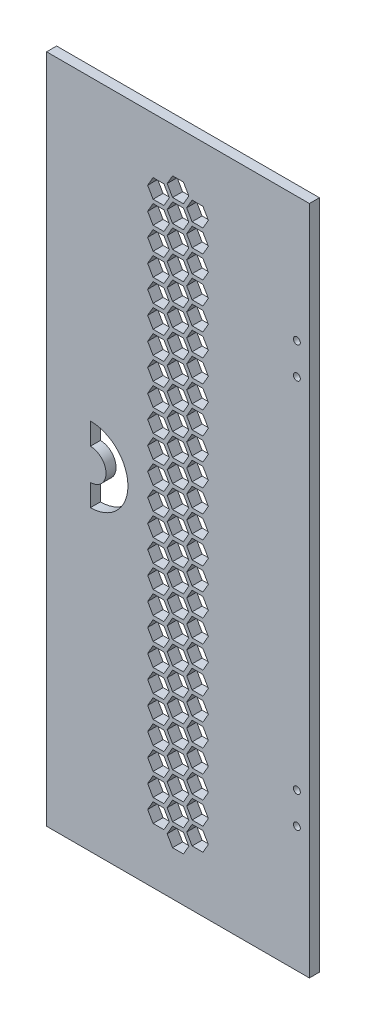
SolidWorks part; units mm, degrees
ref_plane "Front Plane" through (0, 0, 0) normal (0, 0, 1) x (1, 0, 0)
ref_plane "Top Plane" through (0, 0, 0) normal (0, 1, 0) x (1, 0, 0)
ref_plane "Right Plane" through (0, 0, 0) normal (1, 0, 0) x (0, 0, -1)
sketch "Sketch1" plane through (0, 0, 0) normal (0, 0, 1) x (1, 0, 0)
  line L1 (-105, 268) -> (105, 268)
  line L2 (-105, 268) -> (-105, -268)
  line L3 (-105, -268) -> (105, -268)
  line L4 (105, 268) -> (105, -268)
  line L5 (-105, 268) -> (105, -268) construction
  line L6 (-105, -268) -> (105, 268) construction
  circle A10 centre (95, -168) radius 2.75
  circle A11 centre (95, 168) radius 2.75
  circle A12 centre (95, 143) radius 2.75
  circle A13 centre (95, -143) radius 2.75
  point P0 (0, 0)
  point P41 (-6.0047, 6.0048)
  dimension "D3" = 100
  dimension "D1" = 536
  dimension "D2" = 10
  dimension "D4" = 100
  dimension "D7" = 311
  dimension "D5" = 25
  dimension "D8" = 25
  dimension "D9" = 210
extrude "Boss-Extrude1" add sketch "Sketch1" along normal blind 8
sketch "Sketch3" plane through (0, 0, 8) normal (0, 0, 1) x (1, 0, 0)
  line L0 (0, 207) -> (0, 225) construction
  line L1 (24.2487, 216) -> (19.9186, 223.5)
  line L2 (-6.9282, 216) -> (-11.2583, 223.5)
  line L3 (-11.2583, 223.5) -> (-19.9186, 223.5)
  line L4 (-19.9186, 223.5) -> (-24.2487, 216)
  line L5 (19.9186, 223.5) -> (11.2583, 223.5)
  line L6 (11.2583, 223.5) -> (6.9282, 216)
  line L7 (6.9282, 216) -> (11.2583, 208.5)
  line L8 (-24.2487, 216) -> (-19.9186, 208.5)
  line L9 (-19.9186, 208.5) -> (-11.2583, 208.5)
  line L10 (-11.2583, 208.5) -> (-6.9282, 216)
  line L11 (8.6603, 207) -> (4.3301, 214.5)
  line L12 (24.2487, 72) -> (19.9186, 79.5)
  line L13 (-6.9282, 72) -> (-11.2583, 79.5)
  line L14 (-11.2583, 79.5) -> (-19.9186, 79.5)
  line L15 (-19.9186, 79.5) -> (-24.2487, 72)
  line L16 (19.9186, 79.5) -> (11.2583, 79.5)
  line L17 (11.2583, 79.5) -> (6.9282, 72)
  line L18 (6.9282, 72) -> (11.2583, 64.5)
  line L19 (-24.2487, 72) -> (-19.9186, 64.5)
  line L20 (4.3301, 214.5) -> (-4.3301, 214.5)
  line L21 (-4.3301, 214.5) -> (-8.6603, 207)
  line L22 (-8.6603, 207) -> (-4.3301, 199.5)
  line L23 (-4.3301, 199.5) -> (4.3301, 199.5)
  line L24 (4.3301, 199.5) -> (8.6603, 207)
  line L25 (8.6603, 225) -> (4.3301, 232.5)
  line L26 (4.3301, 232.5) -> (-4.3301, 232.5)
  line L27 (-4.3301, 232.5) -> (-8.6603, 225)
  line L28 (-8.6603, 225) -> (-4.3301, 217.5)
  line L29 (-4.3301, 217.5) -> (4.3301, 217.5)
  line L30 (4.3301, 217.5) -> (8.6603, 225)
  line L31 (11.2583, 208.5) -> (19.9186, 208.5)
  line L32 (19.9186, 208.5) -> (24.2487, 216)
  line L33 (0, 225) -> (15.5885, 216) construction
  line L34 (15.5885, 216) -> (0, 207) construction
  line L35 (0, 207) -> (-15.5885, 216) construction
  line L36 (-15.5885, 216) -> (0, 225) construction
  line L37 (24.2487, 198) -> (19.9186, 205.5)
  line L38 (-6.9282, 198) -> (-11.2583, 205.5)
  line L39 (-11.2583, 205.5) -> (-19.9186, 205.5)
  line L40 (-19.9186, 205.5) -> (-24.2487, 198)
  line L41 (19.9186, 205.5) -> (11.2583, 205.5)
  line L42 (11.2583, 205.5) -> (6.9282, 198)
  line L43 (6.9282, 198) -> (11.2583, 190.5)
  line L44 (-24.2487, 198) -> (-19.9186, 190.5)
  line L45 (-19.9186, 190.5) -> (-11.2583, 190.5)
  line L46 (-11.2583, 190.5) -> (-6.9282, 198)
  line L47 (8.6603, 189) -> (4.3301, 196.5)
  line L48 (4.3301, 196.5) -> (-4.3301, 196.5)
  line L49 (-4.3301, 196.5) -> (-8.6603, 189)
  line L50 (-8.6603, 189) -> (-4.3301, 181.5)
  line L51 (-4.3301, 181.5) -> (4.3301, 181.5)
  line L52 (4.3301, 181.5) -> (8.6603, 189)
  line L53 (11.2583, 190.5) -> (19.9186, 190.5)
  line L54 (19.9186, 190.5) -> (24.2487, 198)
  line L55 (15.5885, 198) -> (0, 189) construction
  line L56 (0, 189) -> (-15.5885, 198) construction
  line L57 (24.2487, 180) -> (19.9186, 187.5)
  line L58 (-6.9282, 180) -> (-11.2583, 187.5)
  line L59 (-11.2583, 187.5) -> (-19.9186, 187.5)
  line L60 (-19.9186, 187.5) -> (-24.2487, 180)
  line L61 (19.9186, 187.5) -> (11.2583, 187.5)
  line L62 (11.2583, 187.5) -> (6.9282, 180)
  line L63 (6.9282, 180) -> (11.2583, 172.5)
  line L64 (-24.2487, 180) -> (-19.9186, 172.5)
  line L65 (-19.9186, 172.5) -> (-11.2583, 172.5)
  line L66 (-11.2583, 172.5) -> (-6.9282, 180)
  line L67 (8.6603, 171) -> (4.3301, 178.5)
  line L68 (4.3301, 178.5) -> (-4.3301, 178.5)
  line L69 (-4.3301, 178.5) -> (-8.6603, 171)
  line L70 (-8.6603, 171) -> (-4.3301, 163.5)
  line L71 (-4.3301, 163.5) -> (4.3301, 163.5)
  line L72 (4.3301, 163.5) -> (8.6603, 171)
  line L73 (11.2583, 172.5) -> (19.9186, 172.5)
  line L74 (19.9186, 172.5) -> (24.2487, 180)
  line L75 (15.5885, 180) -> (0, 171) construction
  line L76 (0, 171) -> (-15.5885, 180) construction
  line L77 (24.2487, 162) -> (19.9186, 169.5)
  line L78 (-6.9282, 162) -> (-11.2583, 169.5)
  line L79 (-11.2583, 169.5) -> (-19.9186, 169.5)
  line L80 (-19.9186, 169.5) -> (-24.2487, 162)
  line L81 (19.9186, 169.5) -> (11.2583, 169.5)
  line L82 (11.2583, 169.5) -> (6.9282, 162)
  line L83 (6.9282, 162) -> (11.2583, 154.5)
  line L84 (-24.2487, 162) -> (-19.9186, 154.5)
  line L85 (-19.9186, 154.5) -> (-11.2583, 154.5)
  line L86 (-11.2583, 154.5) -> (-6.9282, 162)
  line L87 (8.6603, 153) -> (4.3301, 160.5)
  line L88 (4.3301, 160.5) -> (-4.3301, 160.5)
  line L89 (-4.3301, 160.5) -> (-8.6603, 153)
  line L90 (-8.6603, 153) -> (-4.3301, 145.5)
  line L91 (-4.3301, 145.5) -> (4.3301, 145.5)
  line L92 (4.3301, 145.5) -> (8.6603, 153)
  line L93 (11.2583, 154.5) -> (19.9186, 154.5)
  line L94 (19.9186, 154.5) -> (24.2487, 162)
  line L95 (15.5885, 162) -> (0, 153) construction
  line L96 (0, 153) -> (-15.5885, 162) construction
  line L97 (24.2487, 144) -> (19.9186, 151.5)
  line L98 (-6.9282, 144) -> (-11.2583, 151.5)
  line L99 (-11.2583, 151.5) -> (-19.9186, 151.5)
  line L100 (-19.9186, 151.5) -> (-24.2487, 144)
  line L101 (19.9186, 151.5) -> (11.2583, 151.5)
  line L102 (11.2583, 151.5) -> (6.9282, 144)
  line L103 (6.9282, 144) -> (11.2583, 136.5)
  line L104 (-24.2487, 144) -> (-19.9186, 136.5)
  line L105 (-19.9186, 136.5) -> (-11.2583, 136.5)
  line L106 (-11.2583, 136.5) -> (-6.9282, 144)
  line L107 (8.6603, 135) -> (4.3301, 142.5)
  line L108 (4.3301, 142.5) -> (-4.3301, 142.5)
  line L109 (-4.3301, 142.5) -> (-8.6603, 135)
  line L110 (-8.6603, 135) -> (-4.3301, 127.5)
  line L111 (-4.3301, 127.5) -> (4.3301, 127.5)
  line L112 (4.3301, 127.5) -> (8.6603, 135)
  line L113 (11.2583, 136.5) -> (19.9186, 136.5)
  line L114 (19.9186, 136.5) -> (24.2487, 144)
  line L115 (15.5885, 144) -> (0, 135) construction
  line L116 (0, 135) -> (-15.5885, 144) construction
  line L117 (24.2487, 126) -> (19.9186, 133.5)
  line L118 (-6.9282, 126) -> (-11.2583, 133.5)
  line L119 (-11.2583, 133.5) -> (-19.9186, 133.5)
  line L120 (-19.9186, 133.5) -> (-24.2487, 126)
  line L121 (19.9186, 133.5) -> (11.2583, 133.5)
  line L122 (11.2583, 133.5) -> (6.9282, 126)
  line L123 (6.9282, 126) -> (11.2583, 118.5)
  line L124 (-24.2487, 126) -> (-19.9186, 118.5)
  line L125 (-19.9186, 118.5) -> (-11.2583, 118.5)
  line L126 (-11.2583, 118.5) -> (-6.9282, 126)
  line L127 (8.6603, 117) -> (4.3301, 124.5)
  line L128 (4.3301, 124.5) -> (-4.3301, 124.5)
  line L129 (-4.3301, 124.5) -> (-8.6603, 117)
  line L130 (-8.6603, 117) -> (-4.3301, 109.5)
  line L131 (-4.3301, 109.5) -> (4.3301, 109.5)
  line L132 (4.3301, 109.5) -> (8.6603, 117)
  line L133 (11.2583, 118.5) -> (19.9186, 118.5)
  line L134 (19.9186, 118.5) -> (24.2487, 126)
  line L135 (15.5885, 126) -> (0, 117) construction
  line L136 (0, 117) -> (-15.5885, 126) construction
  line L137 (24.2487, 108) -> (19.9186, 115.5)
  line L138 (-6.9282, 108) -> (-11.2583, 115.5)
  line L139 (-11.2583, 115.5) -> (-19.9186, 115.5)
  line L140 (-19.9186, 115.5) -> (-24.2487, 108)
  line L141 (19.9186, 115.5) -> (11.2583, 115.5)
  line L142 (11.2583, 115.5) -> (6.9282, 108)
  line L143 (6.9282, 108) -> (11.2583, 100.5)
  line L144 (-24.2487, 108) -> (-19.9186, 100.5)
  line L145 (-19.9186, 100.5) -> (-11.2583, 100.5)
  line L146 (-11.2583, 100.5) -> (-6.9282, 108)
  line L147 (8.6603, 99) -> (4.3301, 106.5)
  line L148 (4.3301, 106.5) -> (-4.3301, 106.5)
  line L149 (-4.3301, 106.5) -> (-8.6603, 99)
  line L150 (-8.6603, 99) -> (-4.3301, 91.5)
  line L151 (-4.3301, 91.5) -> (4.3301, 91.5)
  line L152 (4.3301, 91.5) -> (8.6603, 99)
  line L153 (11.2583, 100.5) -> (19.9186, 100.5)
  line L154 (19.9186, 100.5) -> (24.2487, 108)
  line L155 (15.5885, 108) -> (0, 99) construction
  line L156 (0, 99) -> (-15.5885, 108) construction
  line L157 (24.2487, 90) -> (19.9186, 97.5)
  line L158 (-6.9282, 90) -> (-11.2583, 97.5)
  line L159 (-11.2583, 97.5) -> (-19.9186, 97.5)
  line L160 (-19.9186, 97.5) -> (-24.2487, 90)
  line L161 (19.9186, 97.5) -> (11.2583, 97.5)
  line L162 (11.2583, 97.5) -> (6.9282, 90)
  line L163 (6.9282, 90) -> (11.2583, 82.5)
  line L164 (-24.2487, 90) -> (-19.9186, 82.5)
  line L165 (-19.9186, 82.5) -> (-11.2583, 82.5)
  line L166 (-11.2583, 82.5) -> (-6.9282, 90)
  line L167 (8.6603, 81) -> (4.3301, 88.5)
  line L168 (4.3301, 88.5) -> (-4.3301, 88.5)
  line L169 (-4.3301, 88.5) -> (-8.6603, 81)
  line L170 (-8.6603, 81) -> (-4.3301, 73.5)
  line L171 (-4.3301, 73.5) -> (4.3301, 73.5)
  line L172 (4.3301, 73.5) -> (8.6603, 81)
  line L173 (11.2583, 82.5) -> (19.9186, 82.5)
  line L174 (19.9186, 82.5) -> (24.2487, 90)
  line L175 (15.5885, 90) -> (0, 81) construction
  line L176 (0, 81) -> (-15.5885, 90) construction
  line L177 (-19.9186, 64.5) -> (-11.2583, 64.5)
  line L178 (-11.2583, 64.5) -> (-6.9282, 72)
  line L179 (8.6603, 63) -> (4.3301, 70.5)
  line L180 (4.3301, 70.5) -> (-4.3301, 70.5)
  line L181 (-4.3301, 70.5) -> (-8.6603, 63)
  line L182 (-8.6603, 63) -> (-4.3301, 55.5)
  line L183 (-4.3301, 55.5) -> (4.3301, 55.5)
  line L184 (4.3301, 55.5) -> (8.6603, 63)
  line L185 (11.2583, 64.5) -> (19.9186, 64.5)
  line L186 (19.9186, 64.5) -> (24.2487, 72)
  line L187 (15.5885, 72) -> (0, 63) construction
  line L188 (0, 63) -> (-15.5885, 72) construction
  line L189 (24.2487, 54) -> (19.9186, 61.5)
  line L190 (-6.9282, 54) -> (-11.2583, 61.5)
  line L191 (-11.2583, 61.5) -> (-19.9186, 61.5)
  line L192 (-19.9186, 61.5) -> (-24.2487, 54)
  line L193 (19.9186, 61.5) -> (11.2583, 61.5)
  line L194 (11.2583, 61.5) -> (6.9282, 54)
  line L195 (6.9282, 54) -> (11.2583, 46.5)
  line L196 (-24.2487, 54) -> (-19.9186, 46.5)
  line L197 (-19.9186, 46.5) -> (-11.2583, 46.5)
  line L198 (-11.2583, 46.5) -> (-6.9282, 54)
  line L199 (8.6603, 45) -> (4.3301, 52.5)
  line L200 (4.3301, 52.5) -> (-4.3301, 52.5)
  line L201 (-4.3301, 52.5) -> (-8.6603, 45)
  line L202 (-8.6603, 45) -> (-4.3301, 37.5)
  line L203 (-4.3301, 37.5) -> (4.3301, 37.5)
  line L204 (4.3301, 37.5) -> (8.6603, 45)
  line L205 (11.2583, 46.5) -> (19.9186, 46.5)
  line L206 (19.9186, 46.5) -> (24.2487, 54)
  line L207 (15.5885, 54) -> (0, 45) construction
  line L208 (0, 45) -> (-15.5885, 54) construction
  line L209 (24.2487, 36) -> (19.9186, 43.5)
  line L210 (-6.9282, 36) -> (-11.2583, 43.5)
  line L211 (-11.2583, 43.5) -> (-19.9186, 43.5)
  line L212 (-19.9186, 43.5) -> (-24.2487, 36)
  line L213 (19.9186, 43.5) -> (11.2583, 43.5)
  line L214 (11.2583, 43.5) -> (6.9282, 36)
  line L215 (6.9282, 36) -> (11.2583, 28.5)
  line L216 (-24.2487, 36) -> (-19.9186, 28.5)
  line L217 (-19.9186, 28.5) -> (-11.2583, 28.5)
  line L218 (-11.2583, 28.5) -> (-6.9282, 36)
  line L219 (8.6603, 27) -> (4.3301, 34.5)
  line L220 (4.3301, 34.5) -> (-4.3301, 34.5)
  line L221 (-4.3301, 34.5) -> (-8.6603, 27)
  line L222 (-8.6603, 27) -> (-4.3301, 19.5)
  line L223 (-4.3301, 19.5) -> (4.3301, 19.5)
  line L224 (4.3301, 19.5) -> (8.6603, 27)
  line L225 (11.2583, 28.5) -> (19.9186, 28.5)
  line L226 (19.9186, 28.5) -> (24.2487, 36)
  line L227 (15.5885, 36) -> (0, 27) construction
  line L228 (0, 27) -> (-15.5885, 36) construction
  line L229 (24.2487, 18) -> (19.9186, 25.5)
  line L230 (-6.9282, 18) -> (-11.2583, 25.5)
  line L231 (-11.2583, 25.5) -> (-19.9186, 25.5)
  line L232 (-19.9186, 25.5) -> (-24.2487, 18)
  line L233 (19.9186, 25.5) -> (11.2583, 25.5)
  line L234 (11.2583, 25.5) -> (6.9282, 18)
  line L235 (6.9282, 18) -> (11.2583, 10.5)
  line L236 (-24.2487, 18) -> (-19.9186, 10.5)
  line L237 (-19.9186, 10.5) -> (-11.2583, 10.5)
  line L238 (-11.2583, 10.5) -> (-6.9282, 18)
  line L239 (8.6603, 9) -> (4.3301, 16.5)
  line L240 (4.3301, 16.5) -> (-4.3301, 16.5)
  line L241 (-4.3301, 16.5) -> (-8.6603, 9)
  line L242 (-8.6603, 9) -> (-4.3301, 1.5)
  line L243 (-4.3301, 1.5) -> (4.3301, 1.5)
  line L244 (4.3301, 1.5) -> (8.6603, 9)
  line L245 (11.2583, 10.5) -> (19.9186, 10.5)
  line L246 (19.9186, 10.5) -> (24.2487, 18)
  line L247 (15.5885, 18) -> (0, 9) construction
  line L248 (0, 9) -> (-15.5885, 18) construction
  line L249 (24.2487, 0) -> (19.9186, 7.5)
  line L250 (-6.9282, 0) -> (-11.2583, 7.5)
  line L251 (-11.2583, 7.5) -> (-19.9186, 7.5)
  line L252 (-19.9186, 7.5) -> (-24.2487, 0)
  line L253 (19.9186, 7.5) -> (11.2583, 7.5)
  line L254 (11.2583, 7.5) -> (6.9282, 0)
  line L255 (6.9282, 0) -> (11.2583, -7.5)
  line L256 (-24.2487, 0) -> (-19.9186, -7.5)
  line L257 (-19.9186, -7.5) -> (-11.2583, -7.5)
  line L258 (-11.2583, -7.5) -> (-6.9282, 0)
  line L259 (8.6603, -9) -> (4.3301, -1.5)
  line L260 (4.3301, -1.5) -> (-4.3301, -1.5)
  line L261 (-4.3301, -1.5) -> (-8.6603, -9)
  line L262 (-8.6603, -9) -> (-4.3301, -16.5)
  line L263 (-4.3301, -16.5) -> (4.3301, -16.5)
  line L264 (4.3301, -16.5) -> (8.6603, -9)
  line L265 (11.2583, -7.5) -> (19.9186, -7.5)
  line L266 (19.9186, -7.5) -> (24.2487, 0)
  line L267 (15.5885, 0) -> (0, -9) construction
  line L268 (0, -9) -> (-15.5885, 0) construction
  line L269 (24.2487, -18) -> (19.9186, -10.5)
  line L270 (-6.9282, -18) -> (-11.2583, -10.5)
  line L271 (-11.2583, -10.5) -> (-19.9186, -10.5)
  line L272 (-19.9186, -10.5) -> (-24.2487, -18)
  line L273 (19.9186, -10.5) -> (11.2583, -10.5)
  line L274 (11.2583, -10.5) -> (6.9282, -18)
  line L275 (6.9282, -18) -> (11.2583, -25.5)
  line L276 (-24.2487, -18) -> (-19.9186, -25.5)
  line L277 (-19.9186, -25.5) -> (-11.2583, -25.5)
  line L278 (-11.2583, -25.5) -> (-6.9282, -18)
  line L279 (8.6603, -27) -> (4.3301, -19.5)
  line L280 (4.3301, -19.5) -> (-4.3301, -19.5)
  line L281 (-4.3301, -19.5) -> (-8.6603, -27)
  line L282 (-8.6603, -27) -> (-4.3301, -34.5)
  line L283 (-4.3301, -34.5) -> (4.3301, -34.5)
  line L284 (4.3301, -34.5) -> (8.6603, -27)
  line L285 (11.2583, -25.5) -> (19.9186, -25.5)
  line L286 (19.9186, -25.5) -> (24.2487, -18)
  line L287 (15.5885, -18) -> (0, -27) construction
  line L288 (0, -27) -> (-15.5885, -18) construction
  line L289 (24.2487, -36) -> (19.9186, -28.5)
  line L290 (-6.9282, -36) -> (-11.2583, -28.5)
  line L291 (-11.2583, -28.5) -> (-19.9186, -28.5)
  line L292 (-19.9186, -28.5) -> (-24.2487, -36)
  line L293 (19.9186, -28.5) -> (11.2583, -28.5)
  line L294 (11.2583, -28.5) -> (6.9282, -36)
  line L295 (6.9282, -36) -> (11.2583, -43.5)
  line L296 (-24.2487, -36) -> (-19.9186, -43.5)
  line L297 (-19.9186, -43.5) -> (-11.2583, -43.5)
  line L298 (-11.2583, -43.5) -> (-6.9282, -36)
  line L299 (8.6603, -45) -> (4.3301, -37.5)
  line L300 (4.3301, -37.5) -> (-4.3301, -37.5)
  line L301 (-4.3301, -37.5) -> (-8.6603, -45)
  line L302 (-8.6603, -45) -> (-4.3301, -52.5)
  line L303 (-4.3301, -52.5) -> (4.3301, -52.5)
  line L304 (4.3301, -52.5) -> (8.6603, -45)
  line L305 (11.2583, -43.5) -> (19.9186, -43.5)
  line L306 (19.9186, -43.5) -> (24.2487, -36)
  line L307 (15.5885, -36) -> (0, -45) construction
  line L308 (0, -45) -> (-15.5885, -36) construction
  line L309 (24.2487, -54) -> (19.9186, -46.5)
  line L310 (-6.9282, -54) -> (-11.2583, -46.5)
  line L311 (-11.2583, -46.5) -> (-19.9186, -46.5)
  line L312 (-19.9186, -46.5) -> (-24.2487, -54)
  line L313 (19.9186, -46.5) -> (11.2583, -46.5)
  line L314 (11.2583, -46.5) -> (6.9282, -54)
  line L315 (6.9282, -54) -> (11.2583, -61.5)
  line L316 (-24.2487, -54) -> (-19.9186, -61.5)
  line L317 (-19.9186, -61.5) -> (-11.2583, -61.5)
  line L318 (-11.2583, -61.5) -> (-6.9282, -54)
  line L319 (8.6603, -63) -> (4.3301, -55.5)
  line L320 (4.3301, -55.5) -> (-4.3301, -55.5)
  line L321 (-4.3301, -55.5) -> (-8.6603, -63)
  line L322 (-8.6603, -63) -> (-4.3301, -70.5)
  line L323 (-4.3301, -70.5) -> (4.3301, -70.5)
  line L324 (4.3301, -70.5) -> (8.6603, -63)
  line L325 (11.2583, -61.5) -> (19.9186, -61.5)
  line L326 (19.9186, -61.5) -> (24.2487, -54)
  line L327 (15.5885, -54) -> (0, -63) construction
  line L328 (0, -63) -> (-15.5885, -54) construction
  line L329 (24.2487, -72) -> (19.9186, -64.5)
  line L330 (-6.9282, -72) -> (-11.2583, -64.5)
  line L331 (-11.2583, -64.5) -> (-19.9186, -64.5)
  line L332 (-19.9186, -64.5) -> (-24.2487, -72)
  line L333 (19.9186, -64.5) -> (11.2583, -64.5)
  line L334 (11.2583, -64.5) -> (6.9282, -72)
  line L335 (6.9282, -72) -> (11.2583, -79.5)
  line L336 (-24.2487, -72) -> (-19.9186, -79.5)
  line L337 (-19.9186, -79.5) -> (-11.2583, -79.5)
  line L338 (-11.2583, -79.5) -> (-6.9282, -72)
  line L339 (8.6603, -81) -> (4.3301, -73.5)
  line L340 (4.3301, -73.5) -> (-4.3301, -73.5)
  line L341 (-4.3301, -73.5) -> (-8.6603, -81)
  line L342 (-8.6603, -81) -> (-4.3301, -88.5)
  line L343 (-4.3301, -88.5) -> (4.3301, -88.5)
  line L344 (4.3301, -88.5) -> (8.6603, -81)
  line L345 (11.2583, -79.5) -> (19.9186, -79.5)
  line L346 (19.9186, -79.5) -> (24.2487, -72)
  line L347 (15.5885, -72) -> (0, -81) construction
  line L348 (0, -81) -> (-15.5885, -72) construction
  line L349 (24.2487, -90) -> (19.9186, -82.5)
  line L350 (-6.9282, -90) -> (-11.2583, -82.5)
  line L351 (-11.2583, -82.5) -> (-19.9186, -82.5)
  line L352 (-19.9186, -82.5) -> (-24.2487, -90)
  line L353 (19.9186, -82.5) -> (11.2583, -82.5)
  line L354 (11.2583, -82.5) -> (6.9282, -90)
  line L355 (6.9282, -90) -> (11.2583, -97.5)
  line L356 (-24.2487, -90) -> (-19.9186, -97.5)
  line L357 (-19.9186, -97.5) -> (-11.2583, -97.5)
  line L358 (-11.2583, -97.5) -> (-6.9282, -90)
  line L359 (8.6603, -99) -> (4.3301, -91.5)
  line L360 (4.3301, -91.5) -> (-4.3301, -91.5)
  line L361 (-4.3301, -91.5) -> (-8.6603, -99)
  line L362 (-8.6603, -99) -> (-4.3301, -106.5)
  line L363 (-4.3301, -106.5) -> (4.3301, -106.5)
  line L364 (4.3301, -106.5) -> (8.6603, -99)
  line L365 (11.2583, -97.5) -> (19.9186, -97.5)
  line L366 (19.9186, -97.5) -> (24.2487, -90)
  line L367 (15.5885, -90) -> (0, -99) construction
  line L368 (0, -99) -> (-15.5885, -90) construction
  line L369 (24.2487, -108) -> (19.9186, -100.5)
  line L370 (-6.9282, -108) -> (-11.2583, -100.5)
  line L371 (-11.2583, -100.5) -> (-19.9186, -100.5)
  line L372 (-19.9186, -100.5) -> (-24.2487, -108)
  line L373 (19.9186, -100.5) -> (11.2583, -100.5)
  line L374 (11.2583, -100.5) -> (6.9282, -108)
  line L375 (6.9282, -108) -> (11.2583, -115.5)
  line L376 (-24.2487, -108) -> (-19.9186, -115.5)
  line L377 (-19.9186, -115.5) -> (-11.2583, -115.5)
  line L378 (-11.2583, -115.5) -> (-6.9282, -108)
  line L379 (8.6603, -117) -> (4.3301, -109.5)
  line L380 (4.3301, -109.5) -> (-4.3301, -109.5)
  line L381 (-4.3301, -109.5) -> (-8.6603, -117)
  line L382 (-8.6603, -117) -> (-4.3301, -124.5)
  line L383 (-4.3301, -124.5) -> (4.3301, -124.5)
  line L384 (4.3301, -124.5) -> (8.6603, -117)
  line L385 (11.2583, -115.5) -> (19.9186, -115.5)
  line L386 (19.9186, -115.5) -> (24.2487, -108)
  line L387 (15.5885, -108) -> (0, -117) construction
  line L388 (0, -117) -> (-15.5885, -108) construction
  line L389 (24.2487, -126) -> (19.9186, -118.5)
  line L390 (-6.9282, -126) -> (-11.2583, -118.5)
  line L391 (-11.2583, -118.5) -> (-19.9186, -118.5)
  line L392 (-19.9186, -118.5) -> (-24.2487, -126)
  line L393 (19.9186, -118.5) -> (11.2583, -118.5)
  line L394 (11.2583, -118.5) -> (6.9282, -126)
  line L395 (6.9282, -126) -> (11.2583, -133.5)
  line L396 (-24.2487, -126) -> (-19.9186, -133.5)
  line L397 (-19.9186, -133.5) -> (-11.2583, -133.5)
  line L398 (-11.2583, -133.5) -> (-6.9282, -126)
  line L399 (8.6603, -135) -> (4.3301, -127.5)
  line L400 (4.3301, -127.5) -> (-4.3301, -127.5)
  line L401 (-4.3301, -127.5) -> (-8.6603, -135)
  line L402 (-8.6603, -135) -> (-4.3301, -142.5)
  line L403 (-4.3301, -142.5) -> (4.3301, -142.5)
  line L404 (4.3301, -142.5) -> (8.6603, -135)
  line L405 (11.2583, -133.5) -> (19.9186, -133.5)
  line L406 (19.9186, -133.5) -> (24.2487, -126)
  line L407 (15.5885, -126) -> (0, -135) construction
  line L408 (0, -135) -> (-15.5885, -126) construction
  line L409 (24.2487, -144) -> (19.9186, -136.5)
  line L410 (-6.9282, -144) -> (-11.2583, -136.5)
  line L411 (-11.2583, -136.5) -> (-19.9186, -136.5)
  line L412 (-19.9186, -136.5) -> (-24.2487, -144)
  line L413 (19.9186, -136.5) -> (11.2583, -136.5)
  line L414 (11.2583, -136.5) -> (6.9282, -144)
  line L415 (6.9282, -144) -> (11.2583, -151.5)
  line L416 (-24.2487, -144) -> (-19.9186, -151.5)
  line L417 (-19.9186, -151.5) -> (-11.2583, -151.5)
  line L418 (-11.2583, -151.5) -> (-6.9282, -144)
  line L419 (8.6603, -153) -> (4.3301, -145.5)
  line L420 (4.3301, -145.5) -> (-4.3301, -145.5)
  line L421 (-4.3301, -145.5) -> (-8.6603, -153)
  line L422 (-8.6603, -153) -> (-4.3301, -160.5)
  line L423 (-4.3301, -160.5) -> (4.3301, -160.5)
  line L424 (4.3301, -160.5) -> (8.6603, -153)
  line L425 (11.2583, -151.5) -> (19.9186, -151.5)
  line L426 (19.9186, -151.5) -> (24.2487, -144)
  line L427 (15.5885, -144) -> (0, -153) construction
  line L428 (0, -153) -> (-15.5885, -144) construction
  line L429 (24.2487, -162) -> (19.9186, -154.5)
  line L430 (-6.9282, -162) -> (-11.2583, -154.5)
  line L431 (-11.2583, -154.5) -> (-19.9186, -154.5)
  line L432 (-19.9186, -154.5) -> (-24.2487, -162)
  line L433 (19.9186, -154.5) -> (11.2583, -154.5)
  line L434 (11.2583, -154.5) -> (6.9282, -162)
  line L435 (6.9282, -162) -> (11.2583, -169.5)
  line L436 (-24.2487, -162) -> (-19.9186, -169.5)
  line L437 (-19.9186, -169.5) -> (-11.2583, -169.5)
  line L438 (-11.2583, -169.5) -> (-6.9282, -162)
  line L439 (8.6603, -171) -> (4.3301, -163.5)
  line L440 (4.3301, -163.5) -> (-4.3301, -163.5)
  line L441 (-4.3301, -163.5) -> (-8.6603, -171)
  line L442 (-8.6603, -171) -> (-4.3301, -178.5)
  line L443 (-4.3301, -178.5) -> (4.3301, -178.5)
  line L444 (4.3301, -178.5) -> (8.6603, -171)
  line L445 (11.2583, -169.5) -> (19.9186, -169.5)
  line L446 (19.9186, -169.5) -> (24.2487, -162)
  line L447 (15.5885, -162) -> (0, -171) construction
  line L448 (0, -171) -> (-15.5885, -162) construction
  line L449 (24.2487, -180) -> (19.9186, -172.5)
  line L450 (-6.9282, -180) -> (-11.2583, -172.5)
  line L451 (-11.2583, -172.5) -> (-19.9186, -172.5)
  line L452 (-19.9186, -172.5) -> (-24.2487, -180)
  line L453 (19.9186, -172.5) -> (11.2583, -172.5)
  line L454 (11.2583, -172.5) -> (6.9282, -180)
  line L455 (6.9282, -180) -> (11.2583, -187.5)
  line L456 (-24.2487, -180) -> (-19.9186, -187.5)
  line L457 (-19.9186, -187.5) -> (-11.2583, -187.5)
  line L458 (-11.2583, -187.5) -> (-6.9282, -180)
  line L459 (8.6603, -189) -> (4.3301, -181.5)
  line L460 (4.3301, -181.5) -> (-4.3301, -181.5)
  line L461 (-4.3301, -181.5) -> (-8.6603, -189)
  line L462 (-8.6603, -189) -> (-4.3301, -196.5)
  line L463 (-4.3301, -196.5) -> (4.3301, -196.5)
  line L464 (4.3301, -196.5) -> (8.6603, -189)
  line L465 (11.2583, -187.5) -> (19.9186, -187.5)
  line L466 (19.9186, -187.5) -> (24.2487, -180)
  line L467 (15.5885, -180) -> (0, -189) construction
  line L468 (0, -189) -> (-15.5885, -180) construction
  line L469 (24.2487, -198) -> (19.9186, -190.5)
  line L470 (-6.9282, -198) -> (-11.2583, -190.5)
  line L471 (-11.2583, -190.5) -> (-19.9186, -190.5)
  line L472 (-19.9186, -190.5) -> (-24.2487, -198)
  line L473 (19.9186, -190.5) -> (11.2583, -190.5)
  line L474 (11.2583, -190.5) -> (6.9282, -198)
  line L475 (6.9282, -198) -> (11.2583, -205.5)
  line L476 (-24.2487, -198) -> (-19.9186, -205.5)
  line L477 (-19.9186, -205.5) -> (-11.2583, -205.5)
  line L478 (-11.2583, -205.5) -> (-6.9282, -198)
  line L479 (8.6603, -207) -> (4.3301, -199.5)
  line L480 (4.3301, -199.5) -> (-4.3301, -199.5)
  line L481 (-4.3301, -199.5) -> (-8.6603, -207)
  line L482 (-8.6603, -207) -> (-4.3301, -214.5)
  line L483 (-4.3301, -214.5) -> (4.3301, -214.5)
  line L484 (4.3301, -214.5) -> (8.6603, -207)
  line L485 (11.2583, -205.5) -> (19.9186, -205.5)
  line L486 (19.9186, -205.5) -> (24.2487, -198)
  line L487 (15.5885, -198) -> (0, -207) construction
  line L488 (0, -207) -> (-15.5885, -198) construction
  line L489 (24.2487, -216) -> (19.9186, -208.5)
  line L490 (-6.9282, -216) -> (-11.2583, -208.5)
  line L491 (-11.2583, -208.5) -> (-19.9186, -208.5)
  line L492 (-19.9186, -208.5) -> (-24.2487, -216)
  line L493 (19.9186, -208.5) -> (11.2583, -208.5)
  line L494 (11.2583, -208.5) -> (6.9282, -216)
  line L495 (6.9282, -216) -> (11.2583, -223.5)
  line L496 (-24.2487, -216) -> (-19.9186, -223.5)
  line L497 (-19.9186, -223.5) -> (-11.2583, -223.5)
  line L498 (-11.2583, -223.5) -> (-6.9282, -216)
  line L499 (8.6603, -225) -> (4.3301, -217.5)
  line L500 (4.3301, -217.5) -> (-4.3301, -217.5)
  line L501 (-4.3301, -217.5) -> (-8.6603, -225)
  line L502 (-8.6603, -225) -> (-4.3301, -232.5)
  line L503 (-4.3301, -232.5) -> (4.3301, -232.5)
  line L504 (4.3301, -232.5) -> (8.6603, -225)
  line L505 (11.2583, -223.5) -> (19.9186, -223.5)
  line L506 (19.9186, -223.5) -> (24.2487, -216)
  line L507 (15.5885, -216) -> (0, -225) construction
  line L508 (0, -225) -> (-15.5885, -216) construction
  line L509 (105, 268) -> (-105, 268) construction
  line L511 (105, -268) -> (105, 268) construction
  circle A0 centre (-15.5885, 216) radius 7.5 construction
  circle A1 centre (0, 207) radius 7.5 construction
  circle A2 centre (0, 225) radius 7.5 construction
  circle A3 centre (15.5885, 216) radius 7.5 construction
  circle A4 centre (-15.5885, 198) radius 7.5 construction
  circle A5 centre (0, 189) radius 7.5 construction
  circle A6 centre (15.5885, 198) radius 7.5 construction
  circle A7 centre (-15.5885, 180) radius 7.5 construction
  circle A8 centre (0, 171) radius 7.5 construction
  circle A9 centre (15.5885, 180) radius 7.5 construction
  circle A10 centre (-15.5885, 162) radius 7.5 construction
  circle A11 centre (0, 153) radius 7.5 construction
  circle A12 centre (15.5885, 162) radius 7.5 construction
  circle A13 centre (-15.5885, 144) radius 7.5 construction
  circle A14 centre (0, 135) radius 7.5 construction
  circle A15 centre (15.5885, 144) radius 7.5 construction
  circle A16 centre (-15.5885, 126) radius 7.5 construction
  circle A17 centre (0, 117) radius 7.5 construction
  circle A18 centre (15.5885, 126) radius 7.5 construction
  circle A19 centre (-15.5885, 108) radius 7.5 construction
  circle A20 centre (0, 99) radius 7.5 construction
  circle A21 centre (15.5885, 108) radius 7.5 construction
  circle A22 centre (-15.5885, 90) radius 7.5 construction
  circle A23 centre (0, 81) radius 7.5 construction
  circle A24 centre (15.5885, 90) radius 7.5 construction
  circle A25 centre (-15.5885, 72) radius 7.5 construction
  circle A26 centre (0, 63) radius 7.5 construction
  circle A27 centre (15.5885, 72) radius 7.5 construction
  circle A28 centre (-15.5885, 54) radius 7.5 construction
  circle A29 centre (0, 45) radius 7.5 construction
  circle A30 centre (15.5885, 54) radius 7.5 construction
  circle A31 centre (-15.5885, 36) radius 7.5 construction
  circle A32 centre (0, 27) radius 7.5 construction
  circle A33 centre (15.5885, 36) radius 7.5 construction
  circle A34 centre (-15.5885, 18) radius 7.5 construction
  circle A35 centre (0, 9) radius 7.5 construction
  circle A36 centre (15.5885, 18) radius 7.5 construction
  circle A37 centre (-15.5885, 0) radius 7.5 construction
  circle A38 centre (0, -9) radius 7.5 construction
  circle A39 centre (15.5885, 0) radius 7.5 construction
  circle A40 centre (-15.5885, -18) radius 7.5 construction
  circle A41 centre (0, -27) radius 7.5 construction
  circle A42 centre (15.5885, -18) radius 7.5 construction
  circle A43 centre (-15.5885, -36) radius 7.5 construction
  circle A44 centre (0, -45) radius 7.5 construction
  circle A45 centre (15.5885, -36) radius 7.5 construction
  circle A46 centre (-15.5885, -54) radius 7.5 construction
  circle A47 centre (0, -63) radius 7.5 construction
  circle A48 centre (15.5885, -54) radius 7.5 construction
  circle A49 centre (-15.5885, -72) radius 7.5 construction
  circle A50 centre (0, -81) radius 7.5 construction
  circle A51 centre (15.5885, -72) radius 7.5 construction
  circle A52 centre (-15.5885, -90) radius 7.5 construction
  circle A53 centre (0, -99) radius 7.5 construction
  circle A54 centre (15.5885, -90) radius 7.5 construction
  circle A55 centre (-15.5885, -108) radius 7.5 construction
  circle A56 centre (0, -117) radius 7.5 construction
  circle A57 centre (15.5885, -108) radius 7.5 construction
  circle A58 centre (-15.5885, -126) radius 7.5 construction
  circle A59 centre (0, -135) radius 7.5 construction
  circle A60 centre (15.5885, -126) radius 7.5 construction
  circle A61 centre (-15.5885, -144) radius 7.5 construction
  circle A62 centre (0, -153) radius 7.5 construction
  circle A63 centre (15.5885, -144) radius 7.5 construction
  circle A64 centre (-15.5885, -162) radius 7.5 construction
  circle A65 centre (0, -171) radius 7.5 construction
  circle A66 centre (15.5885, -162) radius 7.5 construction
  circle A67 centre (-15.5885, -180) radius 7.5 construction
  circle A68 centre (0, -189) radius 7.5 construction
  circle A69 centre (15.5885, -180) radius 7.5 construction
  circle A70 centre (-15.5885, -198) radius 7.5 construction
  circle A71 centre (0, -207) radius 7.5 construction
  circle A72 centre (15.5885, -198) radius 7.5 construction
  circle A73 centre (-15.5885, -216) radius 7.5 construction
  circle A74 centre (0, -225) radius 7.5 construction
  circle A75 centre (15.5885, -216) radius 7.5 construction
  dimension "D1" = 3
  dimension "D2" = 15
  dimension "D3" = 3
  dimension "D5" = 3
  dimension "D6" = 43
  dimension "D7" = 105
  dimension "D4" = 25
extrude "Cut-Extrude4" cut sketch "Sketch3" against normal blind 10
sketch "Sketch4" plane through (0, 0, 0) normal (0, 0, -1) x (-1, 0, 0)
  line L0 (70, 30) -> (70, 12.5)
  line L1 (105, 268) -> (105, -268) construction
  line L2 (70, -12.5) -> (70, -30)
  arc A0 (70, 30) -> (70, -30) centre (70, 0) ccw
  arc A1 (70, 12.5) -> (70, -12.5) centre (70, 0) ccw
  dimension "D1" = 30
  dimension "D3" = 25
  dimension "D2" = 35
extrude "Cut-Extrude5" cut sketch "Sketch4" against normal blind 10
